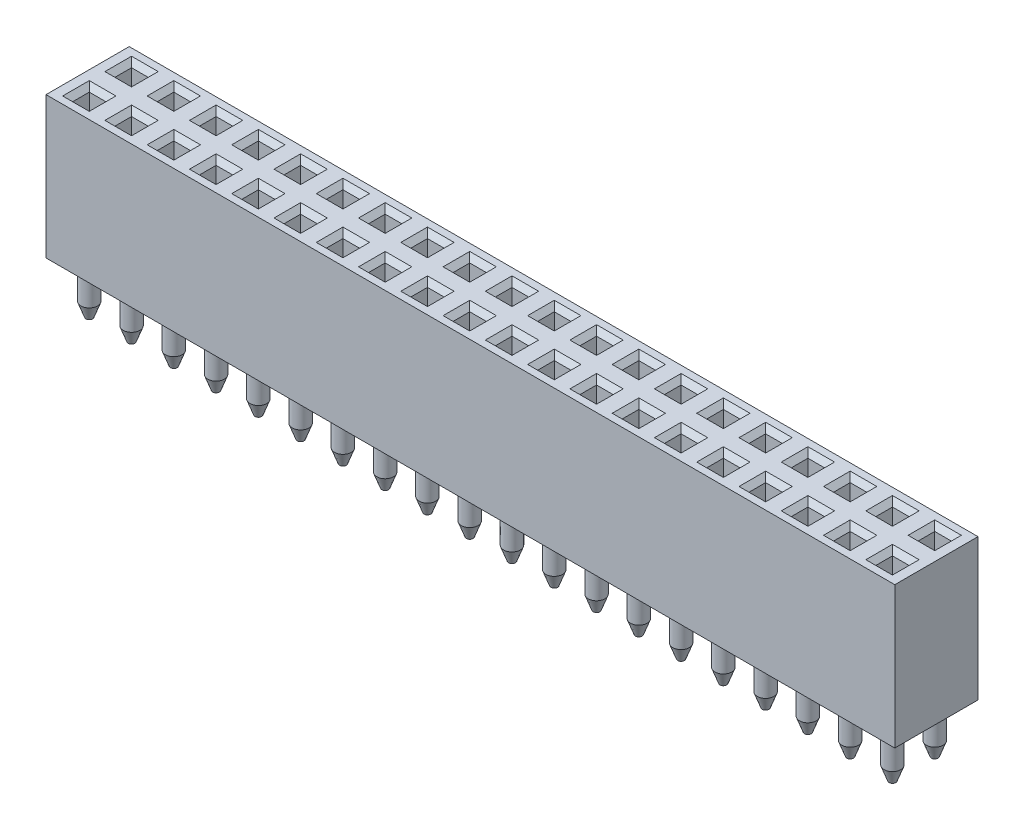
SolidWorks part; units mm, degrees
material "ABS"
ref_plane "Front" through (0, 0, 0) normal (0, 0, 1) x (1, 0, 0)
ref_plane "Top" through (0, 0, 0) normal (0, 1, 0) x (1, 0, 0)
ref_plane "Right" through (0, 0, 0) normal (1, 0, 0) x (0, 0, -1)
sketch "Sketch3" plane through (0, 0, 0) normal (0, 1, 0) x (1, 0, 0)
  line L1 (-25.5, -2.5) -> (25.5, -2.5)
  line L2 (-25.5, -2.5) -> (-25.5, 2.5)
  line L3 (-25.5, 2.5) -> (25.5, 2.5)
  line L4 (25.5, -2.5) -> (25.5, 2.5)
  line L5 (-25.5, -2.5) -> (25.5, 2.5) construction
  line L6 (-25.5, 2.5) -> (25.5, -2.5) construction
  point P0 (0, 0)
  dimension "D1" = 51
  dimension "D2" = 5
extrude "Boss-Extrude2" add sketch "Sketch3" along normal blind 8.5
sketch "Sketch4" plane through (0, 0, 0) normal (0, -1, 0) x (1, 0, 0)
  line L0 (0, 2.5) -> (0, -2.5) construction
  line L1 (-25.5, 2.5) -> (25.5, 2.5) construction
  line L2 (25.5, -2.5) -> (-25.5, -2.5) construction
  line L3 (-25.5, 0) -> (25.5, 0) construction
  line L4 (-25.5, -2.5) -> (-25.5, 2.5) construction
  line L5 (25.5, 2.5) -> (25.5, -2.5) construction
  circle A0 centre (-24.13, -1.27) radius 0.5
  dimension "D1" = 1
  dimension "D2" = 1.27
  dimension "D3" = 24.13
extrude "Boss-Extrude3" add sketch "Sketch4" along normal blind 3
chamfer "Chamfer1" distance 0.3 angle 70 1 edges at (-24.13, -3, -1.77)
pattern_linear "LPattern3" count 20 spacing 2.54 along (1, 0, 0) count 2 spacing 2.54 along (0, 0, 1) of "Boss-Extrude3", "Chamfer1"
sketch "Sketch5" plane through (0, 8.5, 0) normal (0, 1, 0) x (1, 0, 0)
  line L0 (-25.5, 0) -> (25.5, 0) construction
  line L1 (-25.5, 2.5) -> (-25.5, -2.5) construction
  line L2 (25.5, -2.5) -> (25.5, 2.5) construction
  line L3 (0, 2.5) -> (0, -2.5) construction
  line L4 (25.5, 2.5) -> (-25.5, 2.5) construction
  line L5 (-25.5, -2.5) -> (25.5, -2.5) construction
  line L7 (-24.63, -1.77) -> (-23.63, -1.77)
  line L8 (-24.63, -1.77) -> (-24.63, -0.77)
  line L9 (-24.63, -0.77) -> (-23.63, -0.77)
  line L10 (-23.63, -1.77) -> (-23.63, -0.77)
  line L11 (-24.63, -1.77) -> (-23.63, -0.77) construction
  line L12 (-24.63, -0.77) -> (-23.63, -1.77) construction
  point P12 (-24.13, -1.27)
  dimension "D1" = 1
  dimension "D2" = 1
  dimension "D3" = 24.13
  dimension "D4" = 1.27
extrude "Cut-Extrude1" cut sketch "Sketch5" against normal blind 7
chamfer "Chamfer2" distance 0.3 angle 45 4 edges at (-24.13, 8.5, 1.77) (-23.63, 8.5, 1.27) (-24.63, 8.5, 1.27) (-24.13, 8.5, 0.77)
pattern_linear "LPattern6" count 20 spacing 2.54 along (1, 0, 0) count 2 spacing 2.54 along (0, 0, -1) of "Chamfer2", "Cut-Extrude1"
equation "\"D2@Sketch4\"=2.54/2"
equation "\"D3@Sketch4\"=2.54/2+2.54*9"
equation "\"D3@Sketch5\"=2.54/2+2.54*9"
equation "\"D4@Sketch5\"=2.54/2"
